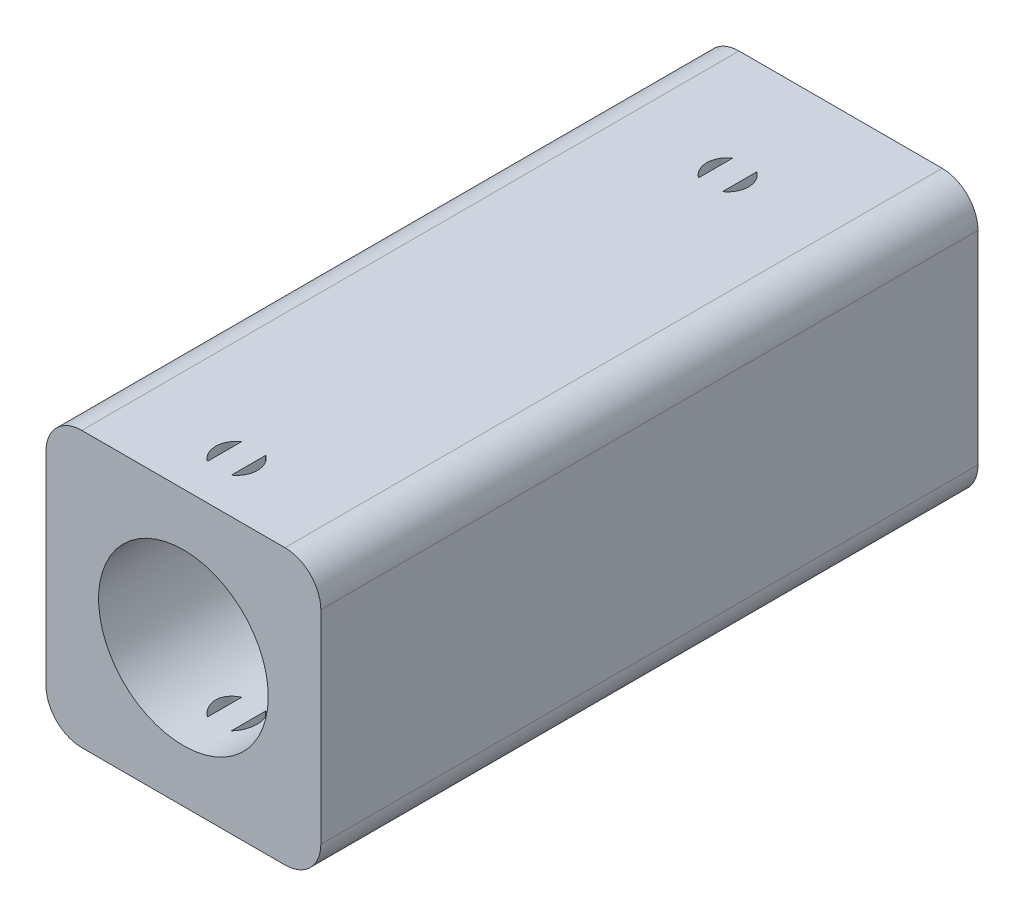
SolidWorks part; units mm, degrees
material "ABS generico"
ref_plane "Piano frontale" through (0, 0, 0) normal (0, 0, 1) x (1, 0, 0)
ref_plane "Piano superiore" through (0, 0, 0) normal (0, 1, 0) x (1, 0, 0)
ref_plane "Piano destro" through (0, 0, 0) normal (1, 0, 0) x (0, 0, -1)
sketch "Schizzo1" plane through (0, 0, 0) normal (0, 0, 1) x (1, 0, 0)
  line L4 (-7.3767, -9.877) -> (-7.3597, -9.8281)
  line L24 (7.9489, 13.813) -> (-15.0511, 13.813)
  line L25 (7.9489, 13.813) -> (7.9489, -9.187)
  line L26 (7.9489, -9.187) -> (-15.0511, -9.187)
  line L27 (-15.0511, 13.813) -> (-15.0511, -9.187)
  dimension "D1" = 23
extrude "Estrusione-Estrusione1" add sketch "Schizzo1" along normal blind 55
sketch "Schizzo18" plane through (0, 0, 0) normal (0, 0, -1) x (-1, 0, 0)
  line L0 (-7.9489, 2.313) -> (15.0511, 2.313) construction
  line L1 (-7.9489, 13.813) -> (-7.9489, -9.187) construction
  line L2 (15.0511, 13.813) -> (15.0511, -9.187) construction
  line L3 (3.5511, 13.813) -> (3.5511, -9.187) construction
  line L4 (-7.9489, 13.813) -> (15.0511, 13.813) construction
  line L5 (-7.9489, -9.187) -> (15.0511, -9.187) construction
  circle A0 centre (3.5511, 2.313) radius 7.1
  dimension "D1" = 14.2
extrude "Taglio-Estrusione12" cut sketch "Schizzo18" against normal up to next
chamfer "Smusso4" distance 1 distance2 3 1 edges at (-10.6511, 2.313, 0)
sketch "Schizzo19" plane through (0, 13.813, 0) normal (0, 1, 0) x (1, 0, 0)
  line L0 (-3.5511, -55) -> (-3.5511, 0) construction
  line L1 (7.9489, -55) -> (-15.0511, -55) construction
  line L2 (7.9489, 0) -> (-15.0511, 0) construction
  circle A0 centre (-3.5511, -50.55) radius 1.75
  circle A1 centre (-3.5511, -9.45) radius 1.75
  dimension "D3" = 3.5
  dimension "D4" = 3.5
  dimension "D1" = 41.1
  dimension "D2" = 4.45
extrude "Taglio-Estrusione13" cut sketch "Schizzo19" against normal through all
sketch "Schizzo20" plane through (0, 13.813, 0) normal (0, 1, 0) x (1, 0, 0)
  line L0 (-2.5511, -48.8) -> (-4.5511, -48.8)
  line L1 (-2.5511, -7.7) -> (-4.5511, -7.7)
  line L2 (-2.5511, -7.7) -> (-2.5511, -11.2)
  line L3 (-2.5511, -11.2) -> (-4.5511, -11.2)
  line L4 (-4.5511, -7.7) -> (-4.5511, -11.2)
  line L5 (-2.5511, -48.8) -> (-2.5511, -52.3)
  line L6 (-2.5511, -52.3) -> (-4.5511, -52.3)
  line L7 (-4.5511, -48.8) -> (-4.5511, -52.3)
  circle A0 centre (-3.5511, -9.45) radius 1.75 construction
  circle A2 centre (-3.5511, -50.55) radius 1.75 construction
  dimension "D1" = 2
  dimension "D2" = 1
  dimension "D3" = 2
  dimension "D4" = 1
  dimension "D5" = 3.5
extrude "Estrusione-Estrusione2" add sketch "Schizzo20" against normal up to surface (4.4708 mm away)
sketch "Schizzo21" plane through (0, -9.187, 0) normal (0, -1, 0) x (1, 0, 0)
  line L1 (-2.5511, 7.7) -> (-4.5511, 7.7)
  line L2 (-2.5511, 7.7) -> (-2.5511, 11.2)
  line L3 (-2.5511, 11.2) -> (-4.5511, 11.2)
  line L4 (-4.5511, 7.7) -> (-4.5511, 11.2)
  line L8 (-2.5511, 48.8) -> (-4.5511, 48.8)
  line L9 (-2.5511, 48.8) -> (-2.5511, 52.3)
  line L10 (-2.5511, 52.3) -> (-4.5511, 52.3)
  line L11 (-4.5511, 48.8) -> (-4.5511, 52.3)
  circle A0 centre (-3.5511, 9.45) radius 1.75 construction
  circle A1 centre (-3.5511, 50.55) radius 1.75 construction
  dimension "D1" = 2
  dimension "D2" = 3.5
  dimension "D3" = 1
  dimension "D4" = 2
  dimension "D5" = 3.5
  dimension "D6" = 1
extrude "Estrusione-Estrusione3" add sketch "Schizzo21" against normal up to surface (4.4708 mm away)
fillet "Raccordo1" radius 3 4 edges at (-15.0511, 13.813, 27.5) (7.9489, 13.813, 27.5) (7.9489, -9.187, 27.5) (-15.0511, -9.187, 27.5)
